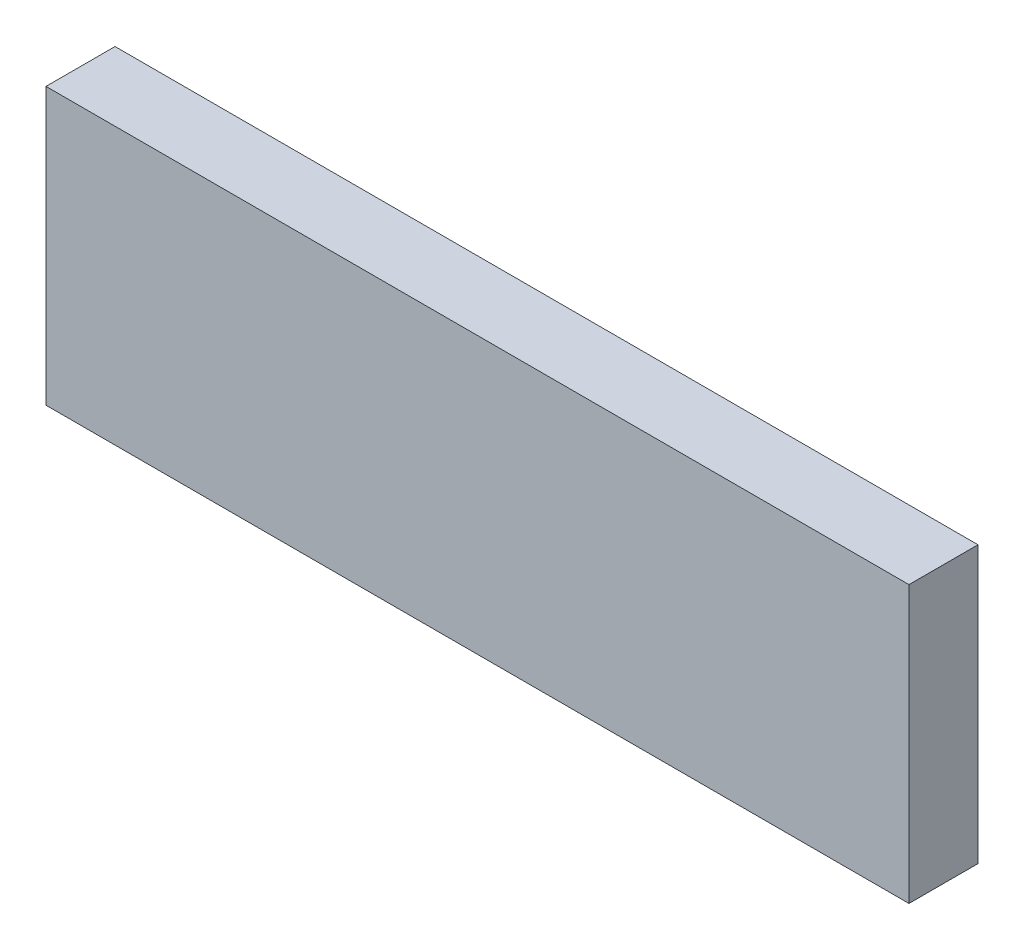
SolidWorks part; units mm, degrees
ref_plane "Front Plane" through (0, 0, 0) normal (0, 0, 1) x (1, 0, 0)
ref_plane "Top Plane" through (0, 0, 0) normal (0, 1, 0) x (1, 0, 0)
ref_plane "Right Plane" through (0, 0, 0) normal (1, 0, 0) x (0, 0, -1)
sketch "Sketch1" plane through (0, 0, 0) normal (0, 0, 1) x (1, 0, 0)
  line L1 (-15.875, -5.08) -> (15.875, -5.08)
  line L2 (-15.875, -5.08) -> (-15.875, 5.08)
  line L3 (-15.875, 5.08) -> (15.875, 5.08)
  line L4 (15.875, -5.08) -> (15.875, 5.08)
  line L5 (-15.875, -5.08) -> (15.875, 5.08) construction
  line L6 (-15.875, 5.08) -> (15.875, -5.08) construction
  point P0 (0, 0)
  dimension "D1" = 10.16
  dimension "D2" = 31.75
extrude "Boss-Extrude1" add sketch "Sketch1" along normal blind 2.54
